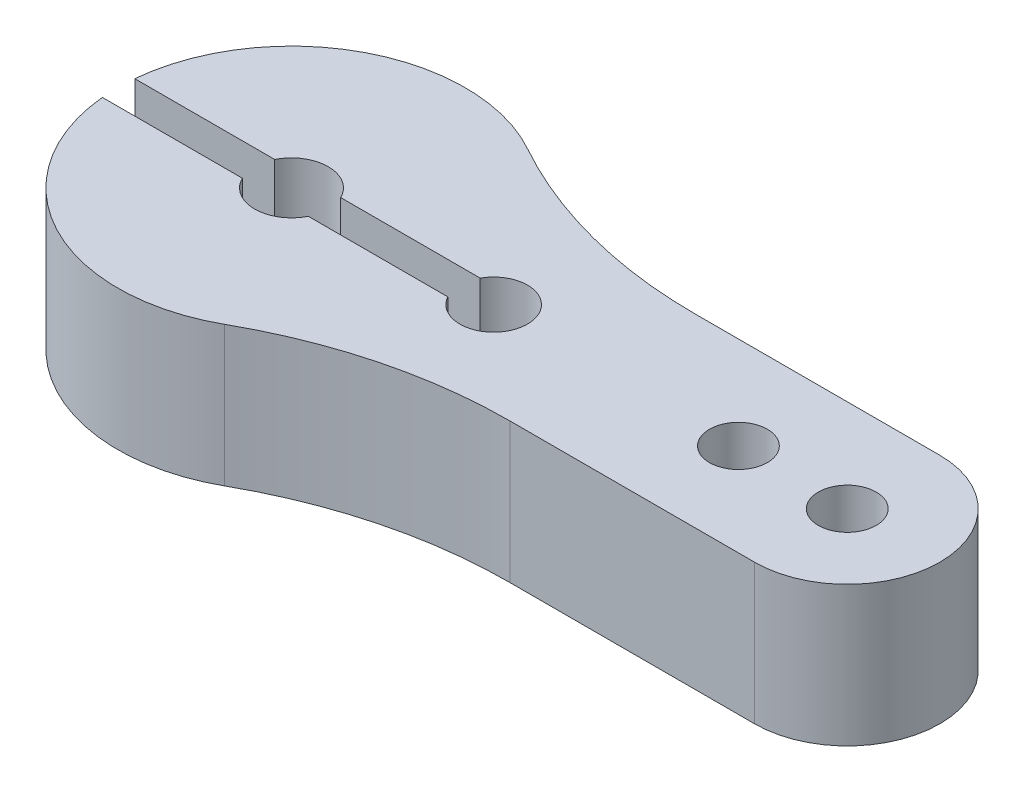
SolidWorks part; units mm, degrees
ref_plane "Front Plane" through (0, 0, 0) normal (0, 0, 1) x (1, 0, 0)
ref_plane "Top Plane" through (0, 0, 0) normal (0, 1, 0) x (1, 0, 0)
ref_plane "Right Plane" through (0, 0, 0) normal (1, 0, 0) x (0, 0, -1)
sketch "Sketch1" plane through (0, 0, 0) normal (0, 1, 0) x (1, 0, 0)
  line L0 (0, 0) -> (19.301, 0) construction
  line L1 (19.301, 0) -> (24, 0) construction
  line L3 (6.3443, -4) -> (24, -4)
  line L4 (6.3443, 4) -> (24, 4)
  arc A0 (6.3443, 4) -> (6.3443, -4) centre (0, 0) ccw
  arc A1 (24, -4) -> (24, 4) centre (24, 0) ccw
  point P3 (0, -4)
  point P10 (0, 4)
  dimension "D1" = 15
  dimension "D2" = 4.699
  dimension "D3" = 24
  dimension "D4" = 8
  dimension "D6" = 24
extrude "Boss-Extrude1" add sketch "Sketch1" along normal blind 6.0452
fillet "Fillet1" radius 20 2 edges at (6.3443, 3.0226, -4) (6.3443, 3.0226, 4)
hole_wizard "Tap Drill for M3x0.5 Tap1" positions "Sketch4" profile "Sketch5" hole size "M3x0.5" standard "ANSI Metric" end condition up to next
sketch "Sketch4" plane through (0, 6.0452, 0) normal (0, 1, 0) x (1, 0, 0)
  point P0 (19.301, 0)
  point P2 (24, 0)
  point P9 (0, 0)
  point P10 (0, 0)
sketch "Sketch5" plane through (19.301, 6.0452, 0) normal (1, 0, 0) x (0, 0, 1)
  line L0 (0, 0) -> (0, 6.0452)
  line L1 (0, 6.0452) -> (1.25, 6.0452)
  line L2 (1.25, 6.0452) -> (1.25, 0)
  line L5 (1.25, 0) -> (0, 0)
  line L11 (0, -6.35) -> (0, 107.95) construction
  dimension "Thru Hole Dia." = 2.5
  dimension "Thru Hole Depth" = 6.0452
sketch "Sketch6" plane through (0, 6.0452, 0) normal (0, 1, 0) x (1, 0, 0)
  line L2 (-7.5, 0) -> (8.7315, 0) construction
  circle A0 centre (0, 0) radius 1.5875
  circle A1 centre (8.7315, 0) radius 1.4605
  arc A2 (3.6616, 6.5455) -> (3.6616, -6.5455) centre (0, 0) ccw construction
  dimension "D1" = 3.175
  dimension "D2" = 2.921
  dimension "D3" = 8.7315
extrude "Cut-Extrude1" cut sketch "Sketch6" against normal up to next
sketch "Sketch7" plane through (0, 6.0452, 0) normal (0, 1, 0) x (1, 0, 0)
  line L0 (7.4496, 0.7) -> (-7.4673, 0.7)
  line L1 (7.4496, -0.7) -> (-7.4673, -0.7)
  line L2 (0, 0) -> (19.301, 0) construction
  circle A0 centre (8.7315, 0) radius 1.4605 construction
  arc A1 (3.6616, 6.5455) -> (3.6616, -6.5455) centre (0, 0) ccw construction
  arc A2 (-7.4673, 0.7) -> (-7.4673, -0.7) centre (0, 0) ccw
  arc A3 (7.4496, 0.7) -> (7.4496, -0.7) centre (8.7315, 0) ccw
  dimension "D1" = 0.7
  dimension "D2" = 1.4
extrude "Cut-Extrude2" cut sketch "Sketch7" against normal up to next
